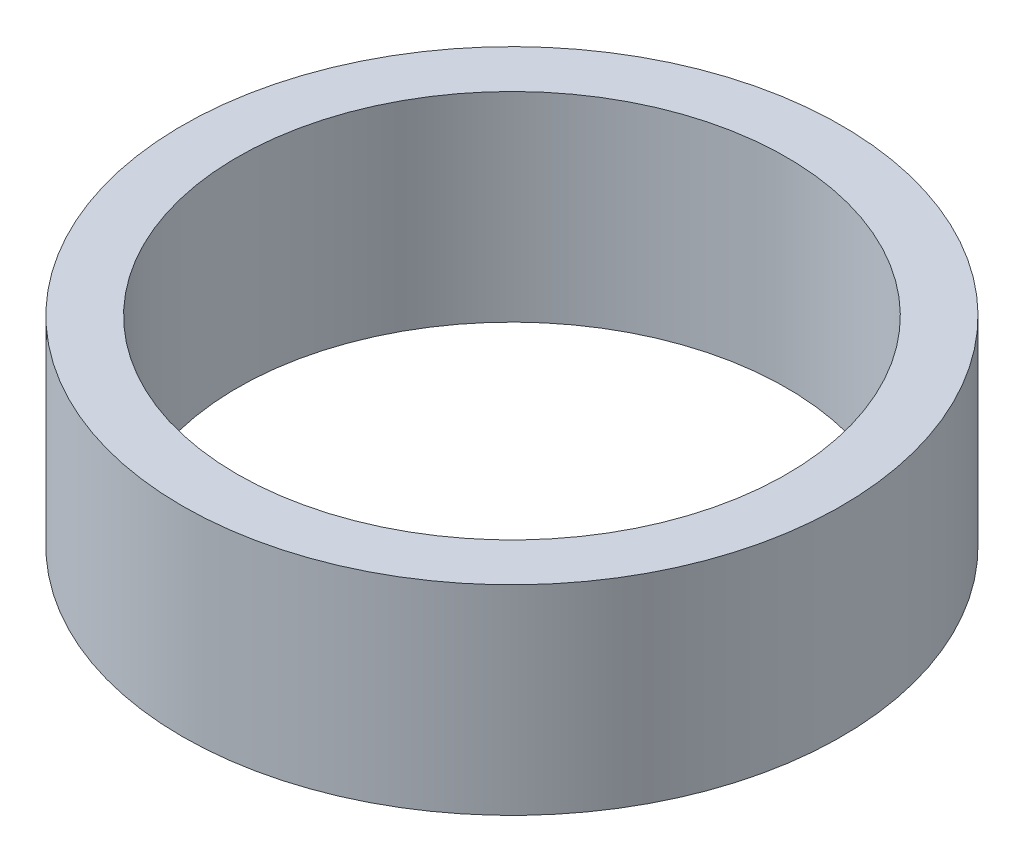
SolidWorks part; units mm, degrees
ref_plane "前视基准面" through (0, 0, 0) normal (0, 0, 1) x (1, 0, 0)
ref_plane "上视基准面" through (0, 0, 0) normal (0, 1, 0) x (1, 0, 0)
ref_plane "右视基准面" through (0, 0, 0) normal (1, 0, 0) x (0, 0, -1)
sketch "草图1" plane through (0, 0, 0) normal (0, 1, 0) x (1, 0, 0)
  circle A0 centre (0, 0) radius 13.75
  circle A1 centre (0, 0) radius 16.5
  dimension "D1" = 33
  dimension "D2" = 27.5
extrude "凸台-拉伸1" add sketch "草图1" along normal blind 10
